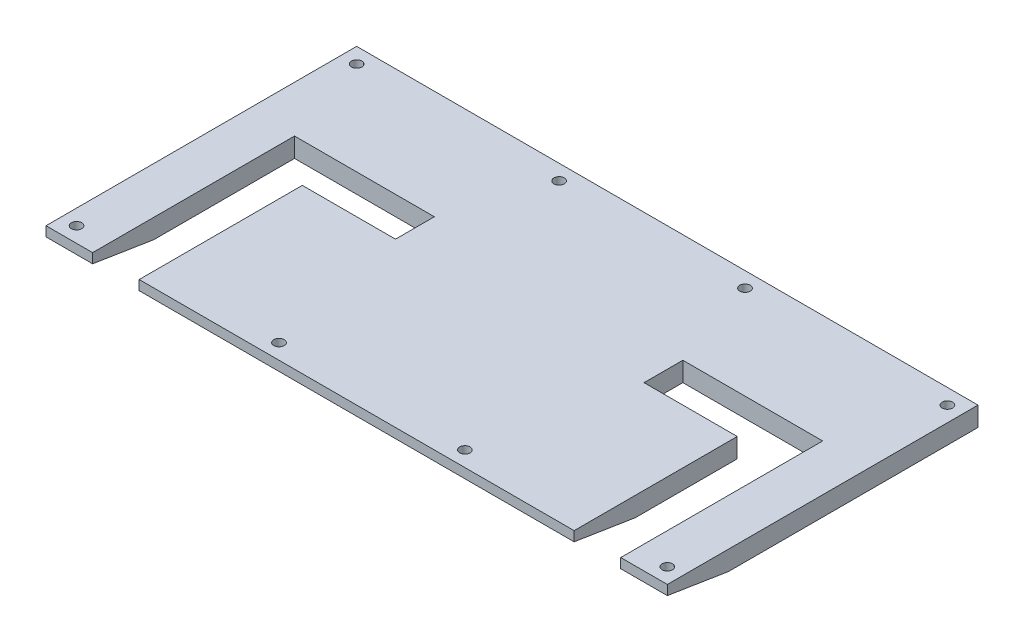
SolidWorks part; units mm, degrees
ref_plane "Front Plane" through (0, 0, 0) normal (0, 0, 1) x (1, 0, 0)
ref_plane "Top Plane" through (0, 0, 0) normal (0, 1, 0) x (1, 0, 0)
ref_plane "Right Plane" through (0, 0, 0) normal (1, 0, 0) x (0, 0, -1)
sketch "Sketch1" plane through (0, 0, 0) normal (0, 1, 0) x (1, 0, 0)
  line L0 (15.24, 53.34) -> (15.24, 66.04)
  line L1 (0, 0) -> (10, 0)
  line L2 (0, 0) -> (0, 101.6)
  line L3 (0, 101.6) -> (76.2, 101.6)
  line L4 (76.2, 0) -> (76.2, 101.6)
  line L5 (15.24, 66.04) -> (60.96, 66.04)
  line L6 (60.96, 66.04) -> (60.96, 0)
  line L7 (60.96, 0) -> (76.2, 0)
  line L9 (10, 0) -> (45.72, 0)
  line L11 (15.24, 53.34) -> (45.72, 53.34)
  line L12 (45.72, 0) -> (45.72, 53.34)
  dimension "D1" = 101.6
  dimension "D2" = 15.24
  dimension "D3" = 66.04
  dimension "D4" = 15.24
  dimension "D5" = 15.24
  dimension "D6" = 12.7
  dimension "D7" = 76.2
extrude "Boss-Extrude1" add sketch "Sketch1" along normal blind 6.35
sketch "Sketch2" plane through (0, 6.35, 0) normal (0, 1, 0) x (1, 0, 0)
  line L0 (38.1, 0) -> (38.1, 68.5972) construction
  line L1 (76.2, 0) -> (76.2, 101.6) construction
  line L2 (0, 50.8) -> (66.4895, 50.8) construction
  line L6 (0, 101.6) -> (0, 0) construction
  line L7 (76.2, 101.6) -> (0, 101.6) construction
  circle A0 centre (5, 96.6) radius 1.7
  circle A1 centre (71.2, 96.6) radius 1.7
  circle A2 centre (71.2, 5) radius 1.7
  circle A3 centre (5, 5) radius 1.7
  point P2 (33.2447, 50.8)
  point P3 (38.1, 34.2986)
  point P20 (76.2, 50.8)
  point P21 (38.1, 101.6)
  dimension "D1" = 3.4
  dimension "D2" = 5
  dimension "D3" = 5
extrude "Cut-Extrude1" cut sketch "Sketch2" against normal through all
ref_plane "Plane1" through (15, 0, 0) normal (-1, 0, 0) x (0, 0, 1)
ref_plane "Plane2" through (61.2, 0, 0) normal (1, 0, 0) x (0, 0, -1)
sketch "Sketch3" plane through (0, 0, 0) normal (-1, 0, 0) x (0, 0, 1)
  line L0 (-101.6, 0) -> (-20, 0)
  line L1 (0, 3.175) -> (0, 6.35)
  line L2 (-20, 0) -> (0, 3.175)
  line L3 (-20, 0) -> (0, 0)
  line L4 (0, 0) -> (0, 3.175)
  point P1 (0, 0)
  line M3 (-101.6, 0) -> (0, 0)
  line M4 (0, 0) -> (0, 6.35)
  dimension "D1" = 20
  dimension "D2" = 3.175
extrude "Cut-Extrude2" cut sketch "Sketch3" against normal through all contours L2 M3 M4
ref_plane "Plane3" through (-25.4, 0, 0) normal (-1, 0, 0) x (0, 0, 1)
mirror "Mirror1" about plane through (-25.4, 0, 0) normal (-1, 0, 0) of bodies 103
sketch "Sketch4" plane through (-50.8, 0, 0) normal (1, 0, 0) x (0, 0, -1)
  line L0 (0, 6.35) -> (101.6, 6.35)
  line L1 (101.6, 6.35) -> (101.6, 0)
  line L2 (101.6, 0) -> (20, 0)
  line L3 (20, 0) -> (0, 3.175)
  line L4 (0, 3.175) -> (0, 6.35)
extrude "Boss-Extrude2" add sketch "Sketch4" along normal up to surface (50.8 mm away) up to face at (0, 3.175, -44.64)
